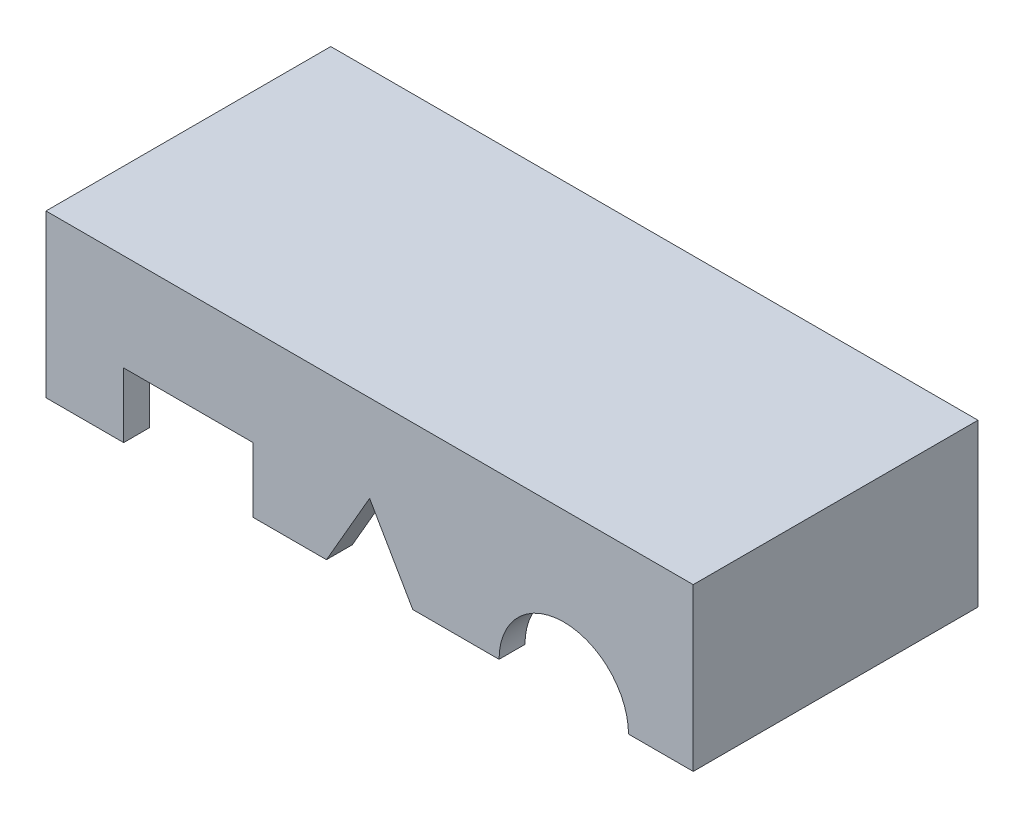
SolidWorks part; units mm, degrees
ref_plane "Front Plane" through (0, 0, 0) normal (0, 0, 1) x (1, 0, 0)
ref_plane "Top Plane" through (0, 0, 0) normal (0, 1, 0) x (1, 0, 0)
ref_plane "Right Plane" through (0, 0, 0) normal (1, 0, 0) x (0, 0, -1)
sketch "Sketch1" plane through (0, 0, 0) normal (0, 0, 1) x (1, 0, 0)
  line L1 (125, -62.5) -> (-125, -62.5)
  line L2 (125, -62.5) -> (125, 62.5)
  line L3 (125, 62.5) -> (-125, 62.5)
  line L4 (-125, -62.5) -> (-125, 62.5)
  line L5 (125, -62.5) -> (-125, 62.5) construction
  line L6 (125, 62.5) -> (-125, -62.5) construction
  line L7 (115, -57.5) -> (-115, -57.5)
  line L8 (115, -57.5) -> (115, 57.5)
  line L9 (115, 57.5) -> (-115, 57.5)
  line L10 (-115, -57.5) -> (-115, 57.5)
  line L11 (115, -57.5) -> (-115, 57.5) construction
  line L12 (115, 57.5) -> (-115, -57.5) construction
  point P0 (0, 0)
  point P6 (0, 0)
  dimension "D1" = 250
  dimension "D2" = 125
  dimension "D3" = 230
extrude "Boss-Extrude1" add sketch "Sketch1" along normal blind 100
sketch "Sketch2" plane through (0, 0, 0) normal (0, 0, -1) x (-1, 0, 0)
  line L1 (125, 62.5) -> (-125, 62.5)
  line L2 (125, 62.5) -> (125, -62.5)
  line L3 (125, -62.5) -> (-125, -62.5)
  line L4 (-125, 62.5) -> (-125, -62.5)
sketch "Sketch3" plane through (0, 0, 100) normal (0, 0, 1) x (1, 0, 0)
  line L0 (-125, 0) -> (125, 0) construction
  line L1 (-125, 62.5) -> (125, 62.5)
  line L2 (-125, 62.5) -> (-125, -62.5)
  line L3 (-125, -62.5) -> (125, -62.5)
  line L4 (125, 62.5) -> (125, -62.5)
  line L5 (0, 62.5) -> (0, -62.5) construction
  line L6 (-25, -14.4338) -> (0, 28.8675)
  line L7 (-95, 25) -> (-45, 25)
  line L8 (-95, 25) -> (-95, -25)
  line L9 (-95, -25) -> (-45, -25)
  line L10 (-45, 25) -> (-45, -25)
  line L11 (-95, 25) -> (-45, -25) construction
  line L12 (-95, -25) -> (-45, 25) construction
  line L14 (-1.3522, 0) -> (0, -1.3522)
  line L18 (0, 28.8675) -> (25, -14.4338)
  line L19 (25, -14.4338) -> (-25, -14.4338)
  line L20 (-25, -14.4338) -> (12.5, 7.2169) construction
  line L21 (25, -14.4338) -> (-12.5, 7.2169) construction
  line L22 (0, 28.8675) -> (0, 0) construction
  circle A0 centre (75, 0) radius 25
  point P10 (-70, 0)
  point P20 (0, 0)
  point P27 (7.7505, -5.3087)
  point P28 (0, 0)
  line M21 (-125, 62.5) -> (-125, -62.5)
  line M22 (-125, -62.5) -> (125, -62.5)
  line M23 (125, -62.5) -> (125, 62.5)
  line M24 (125, 62.5) -> (-125, 62.5)
  line M25 (115, -57.5) -> (-115, -57.5)
  line M26 (-115, -57.5) -> (-115, 57.5)
  line M27 (-115, 57.5) -> (115, 57.5)
  line M28 (115, 57.5) -> (115, -57.5)
  dimension "D2" = 50
  dimension "D3" = 50
  dimension "D1" = 30
  dimension "D4" = 50
  dimension "D5" = 50
  dimension "D6" = 50
  dimension "D7" = 50
  dimension "D8" = 50
extrude "Boss-Extrude4" add sketch "Sketch3" along normal blind 10 contours A0 L7 L10 L9 L8 L18 L19 L6 M25 M28 M27 M26 | M24 M21 M22 M23 M28 M25 M26 M27
sketch "Sketch4" plane through (0, 0, 0) normal (0, 0, 1) x (1, 0, 0)
  line L0 (-138.2338, 0) -> (148.7616, 0)
extrude "Cut-Extrude2" cut sketch "Sketch4" against normal through all and the other way through all flip side to cut
